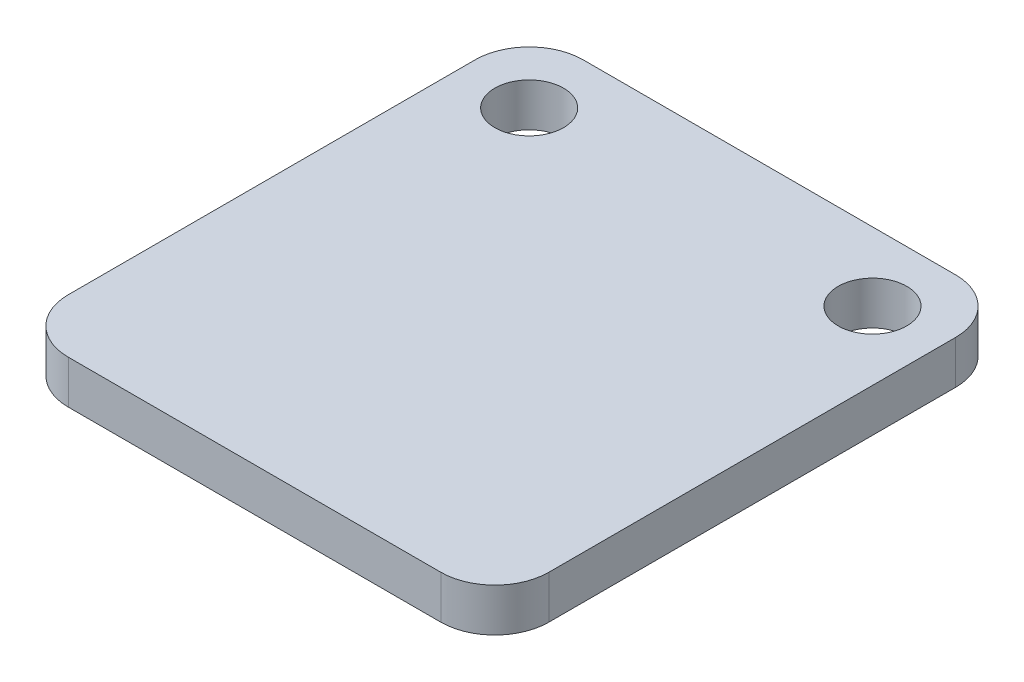
SolidWorks part; units mm, degrees
ref_plane "Front Plane" through (0, 0, 0) normal (0, 0, 1) x (1, 0, 0)
ref_plane "Top Plane" through (0, 0, 0) normal (0, 1, 0) x (1, 0, 0)
ref_plane "Right Plane" through (0, 0, 0) normal (1, 0, 0) x (0, 0, -1)
sketch "Sketch1" plane through (0, 0, 0) normal (0, 1, 0) x (1, 0, 0)
  line L1 (-6.89, 9.525) -> (6.89, 9.525)
  line L2 (-8.89, 7.525) -> (-8.89, -7.525)
  line L3 (-6.89, -9.525) -> (6.89, -9.525)
  line L4 (8.89, 7.525) -> (8.89, -7.525)
  line L5 (-8.89, 9.525) -> (8.89, -9.525) construction
  line L6 (-8.89, -9.525) -> (8.89, 9.525) construction
  arc A0 (-8.89, -7.525) -> (-6.89, -9.525) centre (-6.89, -7.525) ccw
  arc A1 (6.89, -9.525) -> (8.89, -7.525) centre (6.89, -7.525) ccw
  arc A2 (6.89, 9.525) -> (8.89, 7.525) centre (6.89, 7.525) cw
  arc A3 (-6.89, 9.525) -> (-8.89, 7.525) centre (-6.89, 7.525) ccw
  point P0 (0, 0)
  dimension "D3" = 2
  dimension "D1" = 17.78
  dimension "D2" = 19.05
extrude "Boss-Extrude1" add sketch "Sketch1" along normal blind 1.6
sketch "Sketch2" plane through (0, 1.6, 0) normal (0, 1, 0) x (1, 0, 0)
  line L0 (-6.89, -9.525) -> (6.89, -9.525) construction
  line L1 (-8.89, 7.525) -> (-8.89, -7.525) construction
  circle A0 centre (-6.35, 6.985) radius 1.27
  circle A1 centre (6.35, 6.985) radius 1.27
  point P6 (0, 0)
  dimension "D1" = 2.54
  dimension "D2" = 12.7
  dimension "D3" = 16.51
  dimension "D4" = 2.54
extrude "Cut-Extrude1" cut sketch "Sketch2" against normal blind 1.6
